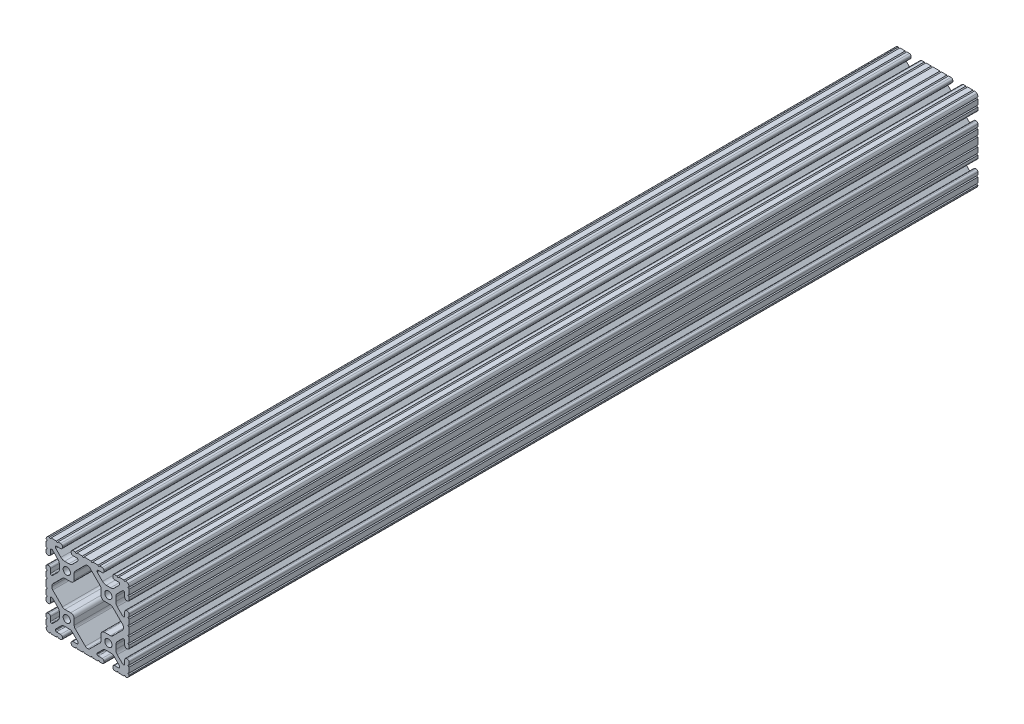
SolidWorks part; units mm, degrees
ref_plane "Front Plane" through (0, 0, 0) normal (0, 0, 1) x (1, 0, 0)
ref_plane "Top Plane" through (0, 0, 0) normal (0, 1, 0) x (1, 0, 0)
ref_plane "Right Plane" through (0, 0, 0) normal (1, 0, 0) x (0, 0, -1)
sketch "Sketch1" plane through (0, 0, 0) normal (0, 0, 1) x (1, 0, 0)
  line L0 (0, 38.1) -> (0, -38.1) construction
  line L1 (-38.1, -38.1) -> (38.1, -38.1) construction
  line L2 (-38.1, -38.1) -> (-38.1, 38.1) construction
  line L3 (-38.1, 38.1) -> (38.1, 38.1) construction
  line L4 (38.1, -38.1) -> (38.1, 38.1) construction
  line L5 (0, 38.1) -> (0, -38.1) construction
  line L6 (-38.1, 0) -> (38.1, 0) construction
  line L7 (-19.05, 19.05) -> (19.05, 19.05) construction
  line L8 (-19.05, 19.05) -> (-19.05, -19.05) construction
  line L9 (-19.05, -19.05) -> (19.05, -19.05) construction
  line L10 (19.05, 19.05) -> (19.05, -19.05) construction
  line L11 (-23.114, 38.1) -> (-23.114, -38.1) construction
  line L12 (-23.114, -38.1) -> (-14.986, 38.1) construction
  line L13 (-14.986, 38.1) -> (-14.986, -38.1) construction
  circle A0 centre (19.05, 19.05) radius 3.3274
  point P0 (0, 0)
  point P9 (0, 0)
  point P12 (-19.05, 0)
  line B0 (-11.3637, -22.8433) -> (-2.0515, -32.1555)
  line B1 (-12.2936, -15.4686) -> (-12.2936, -20.5983)
  line B2 (-20.769, -12.2936) -> (-15.4686, -12.2936)
  line B3 (-31.9021, -2.4756) -> (-23.0141, -11.3637)
  line B4 (-23.0141, 11.3637) -> (-31.9021, 2.4756)
  line B5 (-15.4686, 12.2936) -> (-20.769, 12.2936)
  line B6 (-12.2936, 20.5983) -> (-12.2936, 15.4686)
  line B7 (-2.0515, 32.1555) -> (-11.3637, 22.8433)
  line B8 (11.3637, 22.8433) -> (2.0515, 32.1555)
  line B9 (12.2936, 15.4686) -> (12.2936, 20.5983)
  line B10 (20.769, 12.2936) -> (15.4686, 12.2936)
  line B11 (31.9021, 2.4756) -> (23.0141, 11.3637)
  line B12 (23.0141, -11.3637) -> (31.9021, -2.4756)
  line B13 (15.4686, -12.2936) -> (20.769, -12.2936)
  line B14 (12.2936, -20.5983) -> (12.2936, -15.4686)
  line B15 (2.0515, -32.1555) -> (11.3637, -22.8433)
  line B16 (-4.7773, 38.1) -> (-9.6053, 38.1)
  line B17 (-11.1289, 38.1) -> (-13.4112, 38.1)
  line B18 (-14.986, 36.5252) -> (-14.986, 35.6108)
  line B19 (-13.4112, 34.036) -> (-9.652, 34.036)
  line B20 (-8.763, 33.147) -> (-8.763, 32.4935)
  line B21 (-9.0234, 31.8649) -> (-13.6907, 27.1976)
  line B22 (-17.0493, 25.8064) -> (-21.0507, 25.8064)
  line B23 (-24.4093, 27.1976) -> (-29.1002, 31.8885)
  line B24 (-29.337, 32.7207) -> (-29.337, 33.147)
  line B25 (-28.448, 34.036) -> (-24.6888, 34.036)
  line B26 (-23.114, 35.6108) -> (-23.114, 36.5252)
  line B27 (-24.6888, 38.1) -> (-27.0772, 38.1)
  line B28 (-28.6011, 38.1) -> (-33.4288, 38.1)
  line B29 (-38.1, 33.373) -> (-38.1, 28.5453)
  line B30 (-38.1, 27.0238) -> (-38.1, 24.6302)
  line B31 (-36.5252, 23.0554) -> (-35.6108, 23.0554)
  line B32 (-34.036, 24.6302) -> (-34.036, 28.448)
  line B33 (-33.147, 29.337) -> (-32.6643, 29.337)
  line B34 (-32.0357, 29.0766) -> (-27.1976, 24.2385)
  line B35 (-25.8064, 20.8799) -> (-25.8064, 17.2201)
  line B36 (-27.1976, 13.8615) -> (-31.9489, 9.1101)
  line B37 (-32.7869, 8.763) -> (-33.0603, 8.763)
  line B38 (-34.036, 9.7387) -> (-34.036, 13.4698)
  line B39 (-35.6108, 15.0446) -> (-36.5252, 15.0446)
  line B40 (-38.1, 13.4698) -> (-38.1, 11.075)
  line B41 (-38.1, 9.552) -> (-38.1, 4.7238)
  line B42 (-38.1, 3.2007) -> (-38.1, -3.2007)
  line B43 (-38.1, -4.7238) -> (-38.1, -9.552)
  line B44 (-38.1, -11.075) -> (-38.1, -13.4698)
  line B45 (-36.5252, -15.0446) -> (-35.6108, -15.0446)
  line B46 (-34.036, -13.4698) -> (-34.036, -9.7387)
  line B47 (-33.0603, -8.763) -> (-32.7869, -8.763)
  line B48 (-31.9489, -9.1101) -> (-27.1976, -13.8615)
  line B49 (-25.8064, -17.2201) -> (-25.8064, -20.8799)
  line B50 (-27.1976, -24.2385) -> (-32.0357, -29.0766)
  line B51 (-32.6643, -29.337) -> (-33.147, -29.337)
  line B52 (-34.036, -28.448) -> (-34.036, -24.6302)
  line B53 (-35.6108, -23.0554) -> (-36.5252, -23.0554)
  line B54 (-38.1, -24.6302) -> (-38.1, -27.0238)
  line B55 (-38.1, -28.5453) -> (-38.1, -33.373)
  line B56 (-33.4288, -38.1) -> (-28.6011, -38.1)
  line B57 (-27.0772, -38.1) -> (-24.6888, -38.1)
  line B58 (-23.114, -36.5252) -> (-23.114, -35.6108)
  line B59 (-24.6888, -34.036) -> (-28.448, -34.036)
  line B60 (-29.337, -33.147) -> (-29.337, -32.7207)
  line B61 (-29.1002, -31.8885) -> (-24.4093, -27.1976)
  line B62 (-21.0507, -25.8064) -> (-17.0493, -25.8064)
  line B63 (-13.6907, -27.1976) -> (-9.0234, -31.8649)
  line B64 (-8.763, -32.4935) -> (-8.763, -33.147)
  line B65 (-9.652, -34.036) -> (-13.4112, -34.036)
  line B66 (-14.986, -35.6108) -> (-14.986, -36.5252)
  line B67 (-13.4112, -38.1) -> (-11.1289, -38.1)
  line B68 (-9.6053, -38.1) -> (-4.7773, -38.1)
  line B69 (-3.2537, -38.1) -> (3.2537, -38.1)
  line B70 (4.7773, -38.1) -> (9.6053, -38.1)
  line B71 (11.1289, -38.1) -> (13.4112, -38.1)
  line B72 (14.986, -36.5252) -> (14.986, -35.6108)
  line B73 (13.4112, -34.036) -> (9.652, -34.036)
  line B74 (8.763, -33.147) -> (8.763, -32.4935)
  line B75 (9.0234, -31.8649) -> (13.6907, -27.1976)
  line B76 (17.0493, -25.8064) -> (21.0507, -25.8064)
  line B77 (24.4093, -27.1976) -> (29.1002, -31.8885)
  line B78 (29.337, -32.7207) -> (29.337, -33.147)
  line B79 (28.448, -34.036) -> (24.6888, -34.036)
  line B80 (23.114, -35.6108) -> (23.114, -36.5252)
  line B81 (24.6888, -38.1) -> (27.0772, -38.1)
  line B82 (28.6011, -38.1) -> (33.4288, -38.1)
  line B83 (38.1, -33.373) -> (38.1, -28.5453)
  line B84 (38.1, -27.0238) -> (38.1, -24.6302)
  line B85 (36.5252, -23.0554) -> (35.6108, -23.0554)
  line B86 (34.036, -24.6302) -> (34.036, -28.448)
  line B87 (33.147, -29.337) -> (32.6643, -29.337)
  line B88 (32.0357, -29.0766) -> (27.1976, -24.2385)
  line B89 (25.8064, -20.8799) -> (25.8064, -17.2201)
  line B90 (27.1976, -13.8615) -> (31.9489, -9.1101)
  line B91 (32.7869, -8.763) -> (33.0603, -8.763)
  line B92 (34.036, -9.7387) -> (34.036, -13.4698)
  line B93 (35.6108, -15.0446) -> (36.5252, -15.0446)
  line B94 (38.1, -13.4698) -> (38.1, -11.075)
  line B95 (38.1, -9.552) -> (38.1, -4.7238)
  line B96 (38.1, -3.2007) -> (38.1, 3.2007)
  line B97 (38.1, 4.7238) -> (38.1, 9.552)
  line B98 (38.1, 11.075) -> (38.1, 13.4698)
  line B99 (36.5252, 15.0446) -> (35.6108, 15.0446)
  line B100 (34.036, 13.4698) -> (34.036, 9.7387)
  line B101 (33.0603, 8.763) -> (32.7869, 8.763)
  line B102 (31.9489, 9.1101) -> (27.1976, 13.8615)
  line B103 (25.8064, 17.2201) -> (25.8064, 20.8799)
  line B104 (27.1976, 24.2385) -> (32.0357, 29.0766)
  line B105 (32.6643, 29.337) -> (33.147, 29.337)
  line B106 (34.036, 28.448) -> (34.036, 24.6302)
  line B107 (35.6108, 23.0554) -> (36.5252, 23.0554)
  line B108 (38.1, 24.6302) -> (38.1, 27.0238)
  line B109 (38.1, 28.5453) -> (38.1, 33.373)
  line B110 (33.4288, 38.1) -> (28.6011, 38.1)
  line B111 (27.0772, 38.1) -> (24.6888, 38.1)
  line B112 (23.114, 36.5252) -> (23.114, 35.6108)
  line B113 (24.6888, 34.036) -> (28.448, 34.036)
  line B114 (29.337, 33.147) -> (29.337, 32.7207)
  line B115 (29.1002, 31.8885) -> (24.4093, 27.1976)
  line B116 (21.0507, 25.8064) -> (17.0493, 25.8064)
  line B117 (13.6907, 27.1976) -> (9.0234, 31.8649)
  line B118 (8.763, 32.4935) -> (8.763, 33.147)
  line B119 (9.652, 34.036) -> (13.4112, 34.036)
  line B120 (14.986, 35.6108) -> (14.986, 36.5252)
  line B121 (13.4112, 38.1) -> (11.1289, 38.1)
  line B122 (9.6053, 38.1) -> (4.7773, 38.1)
  line B123 (3.2537, 38.1) -> (-3.2537, 38.1)
  circle B124 centre (-19.05, 19.05) radius 3.3274
  circle B125 centre (-19.05, -19.05) radius 3.3274
  circle B126 centre (19.05, -19.05) radius 3.3274
  circle B127 centre (19.05, 19.05) radius 3.3274
  arc B128 (0, -33.011) -> (2.0515, -32.1555) centre (-0.0139, -30.09) ccw
  arc B129 (-2.0515, -32.1555) -> (0, -33.011) centre (0.0139, -30.09) ccw
  arc B130 (-12.2936, -20.5983) -> (-11.3637, -22.8433) centre (-9.1186, -20.5983) ccw
  arc B131 (-12.2936, -15.4686) -> (-15.4686, -12.2936) centre (-15.4686, -15.4686) ccw
  arc B132 (-23.0141, -11.3637) -> (-20.769, -12.2936) centre (-20.769, -9.1186) ccw
  arc B133 (-32.7287, 0) -> (-31.9021, -2.4756) centre (-29.8367, -0.4102) ccw
  arc B134 (-31.9021, 2.4756) -> (-32.7287, 0) centre (-29.8367, 0.4102) ccw
  arc B135 (-20.769, 12.2936) -> (-23.0141, 11.3637) centre (-20.769, 9.1186) ccw
  arc B136 (-15.4686, 12.2936) -> (-12.2936, 15.4686) centre (-15.4686, 15.4686) ccw
  arc B137 (-11.3637, 22.8433) -> (-12.2936, 20.5983) centre (-9.1186, 20.5983) ccw
  arc B138 (0, 33.011) -> (-2.0515, 32.1555) centre (0.0139, 30.09) ccw
  arc B139 (2.0515, 32.1555) -> (0, 33.011) centre (-0.0139, 30.09) ccw
  arc B140 (12.2936, 20.5983) -> (11.3637, 22.8433) centre (9.1186, 20.5983) ccw
  arc B141 (12.2936, 15.4686) -> (15.4686, 12.2936) centre (15.4686, 15.4686) ccw
  arc B142 (23.0141, 11.3637) -> (20.769, 12.2936) centre (20.769, 9.1186) ccw
  arc B143 (32.7287, 0) -> (31.9021, 2.4756) centre (29.8367, 0.4102) ccw
  arc B144 (31.9021, -2.4756) -> (32.7287, 0) centre (29.8367, -0.4102) ccw
  arc B145 (20.769, -12.2936) -> (23.0141, -11.3637) centre (20.769, -9.1186) ccw
  arc B146 (15.4686, -12.2936) -> (12.2936, -15.4686) centre (15.4686, -15.4686) ccw
  arc B147 (11.3637, -22.8433) -> (12.2936, -20.5983) centre (9.1186, -20.5983) ccw
  arc B148 (-4.7773, 38.1) -> (-3.2537, 38.1) centre (-4.0155, 38.0824) ccw
  arc B149 (-11.1289, 38.1) -> (-9.6053, 38.1) centre (-10.3671, 38.0824) ccw
  arc B150 (-13.4112, 38.1) -> (-14.986, 36.5252) centre (-13.4112, 36.5252) ccw
  arc B151 (-14.986, 35.6108) -> (-13.4112, 34.036) centre (-13.4112, 35.6108) ccw
  arc B152 (-8.763, 33.147) -> (-9.652, 34.036) centre (-9.652, 33.147) ccw
  arc B153 (-9.0234, 31.8649) -> (-8.763, 32.4935) centre (-9.652, 32.4935) ccw
  arc B154 (-17.0493, 25.8064) -> (-13.6907, 27.1976) centre (-17.0493, 30.5562) ccw
  arc B155 (-24.4093, 27.1976) -> (-21.0507, 25.8064) centre (-21.0507, 30.5562) ccw
  arc B156 (-29.337, 32.7207) -> (-29.1002, 31.8885) centre (-28.4716, 32.5172) ccw
  arc B157 (-28.448, 34.036) -> (-29.337, 33.147) centre (-28.448, 33.147) ccw
  arc B158 (-24.6888, 34.036) -> (-23.114, 35.6108) centre (-24.6888, 35.6108) ccw
  arc B159 (-23.114, 36.5252) -> (-24.6888, 38.1) centre (-24.6888, 36.5252) ccw
  arc B160 (-28.6011, 38.1) -> (-27.0772, 38.1) centre (-27.8392, 38.0824) ccw
  arc B161 (-34.9527, 38.1) -> (-33.4288, 38.1) centre (-34.1907, 38.0824) ccw
  arc B162 (-34.9527, 38.1) -> (-37.0861, 37.1826) centre (-34.8521, 34.9266) ccw
  arc B163 (-37.0861, 37.1826) -> (-38.1, 34.8455) centre (-34.925, 34.8566) ccw
  arc B164 (-38.1, 33.373) -> (-38.1, 34.8455) centre (-37.9035, 34.1092) ccw
  arc B165 (-38.1, 27.0238) -> (-38.1, 28.5453) centre (-37.9035, 27.7845) ccw
  arc B166 (-38.1, 24.6302) -> (-36.5252, 23.0554) centre (-36.5252, 24.6302) ccw
  arc B167 (-35.6108, 23.0554) -> (-34.036, 24.6302) centre (-35.6108, 24.6302) ccw
  arc B168 (-33.147, 29.337) -> (-34.036, 28.448) centre (-33.147, 28.448) ccw
  arc B169 (-32.0357, 29.0766) -> (-32.6643, 29.337) centre (-32.6643, 28.448) ccw
  arc B170 (-25.8064, 20.8799) -> (-27.1976, 24.2385) centre (-30.5562, 20.8799) ccw
  arc B171 (-27.1976, 13.8615) -> (-25.8064, 17.2201) centre (-30.5562, 17.2201) ccw
  arc B172 (-32.7869, 8.763) -> (-31.9489, 9.1101) centre (-32.7869, 9.9481) ccw
  arc B173 (-34.036, 9.7387) -> (-33.0603, 8.763) centre (-33.0603, 9.7387) ccw
  arc B174 (-34.036, 13.4698) -> (-35.6108, 15.0446) centre (-35.6108, 13.4698) ccw
  arc B175 (-36.5252, 15.0446) -> (-38.1, 13.4698) centre (-36.5252, 13.4698) ccw
  arc B176 (-38.1, 9.552) -> (-38.1, 11.075) centre (-37.9035, 10.3135) ccw
  arc B177 (-38.1, 3.2007) -> (-38.1, 4.7238) centre (-37.9035, 3.9622) ccw
  arc B178 (-38.1, -4.7238) -> (-38.1, -3.2007) centre (-37.9035, -3.9622) ccw
  arc B179 (-38.1, -11.075) -> (-38.1, -9.552) centre (-37.9035, -10.3135) ccw
  arc B180 (-38.1, -13.4698) -> (-36.5252, -15.0446) centre (-36.5252, -13.4698) ccw
  arc B181 (-35.6108, -15.0446) -> (-34.036, -13.4698) centre (-35.6108, -13.4698) ccw
  arc B182 (-33.0603, -8.763) -> (-34.036, -9.7387) centre (-33.0603, -9.7387) ccw
  arc B183 (-31.9489, -9.1101) -> (-32.7869, -8.763) centre (-32.7869, -9.9481) ccw
  arc B184 (-25.8064, -17.2201) -> (-27.1976, -13.8615) centre (-30.5562, -17.2201) ccw
  arc B185 (-27.1976, -24.2385) -> (-25.8064, -20.8799) centre (-30.5562, -20.8799) ccw
  arc B186 (-32.6643, -29.337) -> (-32.0357, -29.0766) centre (-32.6643, -28.448) ccw
  arc B187 (-34.036, -28.448) -> (-33.147, -29.337) centre (-33.147, -28.448) ccw
  arc B188 (-34.036, -24.6302) -> (-35.6108, -23.0554) centre (-35.6108, -24.6302) ccw
  arc B189 (-36.5252, -23.0554) -> (-38.1, -24.6302) centre (-36.5252, -24.6302) ccw
  arc B190 (-38.1, -28.5453) -> (-38.1, -27.0238) centre (-37.9035, -27.7845) ccw
  arc B191 (-38.1, -34.8455) -> (-38.1, -33.373) centre (-37.9035, -34.1092) ccw
  arc B192 (-38.1, -34.8455) -> (-37.0861, -37.1826) centre (-34.925, -34.8566) ccw
  arc B193 (-37.0861, -37.1826) -> (-34.9527, -38.1) centre (-34.8521, -34.9266) ccw
  arc B194 (-33.4288, -38.1) -> (-34.9527, -38.1) centre (-34.1907, -38.0824) ccw
  arc B195 (-27.0772, -38.1) -> (-28.6011, -38.1) centre (-27.8392, -38.0824) ccw
  arc B196 (-24.6888, -38.1) -> (-23.114, -36.5252) centre (-24.6888, -36.5252) ccw
  arc B197 (-23.114, -35.6108) -> (-24.6888, -34.036) centre (-24.6888, -35.6108) ccw
  arc B198 (-29.337, -33.147) -> (-28.448, -34.036) centre (-28.448, -33.147) ccw
  arc B199 (-29.1002, -31.8885) -> (-29.337, -32.7207) centre (-28.4716, -32.5172) ccw
  arc B200 (-21.0507, -25.8064) -> (-24.4093, -27.1976) centre (-21.0507, -30.5562) ccw
  arc B201 (-13.6907, -27.1976) -> (-17.0493, -25.8064) centre (-17.0493, -30.5562) ccw
  arc B202 (-8.763, -32.4935) -> (-9.0234, -31.8649) centre (-9.652, -32.4935) ccw
  arc B203 (-9.652, -34.036) -> (-8.763, -33.147) centre (-9.652, -33.147) ccw
  arc B204 (-13.4112, -34.036) -> (-14.986, -35.6108) centre (-13.4112, -35.6108) ccw
  arc B205 (-14.986, -36.5252) -> (-13.4112, -38.1) centre (-13.4112, -36.5252) ccw
  arc B206 (-9.6053, -38.1) -> (-11.1289, -38.1) centre (-10.3671, -38.0824) ccw
  arc B207 (-3.2537, -38.1) -> (-4.7773, -38.1) centre (-4.0155, -38.0824) ccw
  arc B208 (4.7773, -38.1) -> (3.2537, -38.1) centre (4.0155, -38.0824) ccw
  arc B209 (11.1289, -38.1) -> (9.6053, -38.1) centre (10.3671, -38.0824) ccw
  arc B210 (13.4112, -38.1) -> (14.986, -36.5252) centre (13.4112, -36.5252) ccw
  arc B211 (14.986, -35.6108) -> (13.4112, -34.036) centre (13.4112, -35.6108) ccw
  arc B212 (8.763, -33.147) -> (9.652, -34.036) centre (9.652, -33.147) ccw
  arc B213 (9.0234, -31.8649) -> (8.763, -32.4935) centre (9.652, -32.4935) ccw
  arc B214 (17.0493, -25.8064) -> (13.6907, -27.1976) centre (17.0493, -30.5562) ccw
  arc B215 (24.4093, -27.1976) -> (21.0507, -25.8064) centre (21.0507, -30.5562) ccw
  arc B216 (29.337, -32.7207) -> (29.1002, -31.8885) centre (28.4716, -32.5172) ccw
  arc B217 (28.448, -34.036) -> (29.337, -33.147) centre (28.448, -33.147) ccw
  arc B218 (24.6888, -34.036) -> (23.114, -35.6108) centre (24.6888, -35.6108) ccw
  arc B219 (23.114, -36.5252) -> (24.6888, -38.1) centre (24.6888, -36.5252) ccw
  arc B220 (28.6011, -38.1) -> (27.0772, -38.1) centre (27.8392, -38.0824) ccw
  arc B221 (34.9527, -38.1) -> (33.4288, -38.1) centre (34.1907, -38.0824) ccw
  arc B222 (34.9527, -38.1) -> (37.0861, -37.1826) centre (34.8521, -34.9266) ccw
  arc B223 (37.0861, -37.1826) -> (38.1, -34.8455) centre (34.925, -34.8566) ccw
  arc B224 (38.1, -33.373) -> (38.1, -34.8455) centre (37.9035, -34.1092) ccw
  arc B225 (38.1, -27.0238) -> (38.1, -28.5453) centre (37.9035, -27.7845) ccw
  arc B226 (38.1, -24.6302) -> (36.5252, -23.0554) centre (36.5252, -24.6302) ccw
  arc B227 (35.6108, -23.0554) -> (34.036, -24.6302) centre (35.6108, -24.6302) ccw
  arc B228 (33.147, -29.337) -> (34.036, -28.448) centre (33.147, -28.448) ccw
  arc B229 (32.0357, -29.0766) -> (32.6643, -29.337) centre (32.6643, -28.448) ccw
  arc B230 (25.8064, -20.8799) -> (27.1976, -24.2385) centre (30.5562, -20.8799) ccw
  arc B231 (27.1976, -13.8615) -> (25.8064, -17.2201) centre (30.5562, -17.2201) ccw
  arc B232 (32.7869, -8.763) -> (31.9489, -9.1101) centre (32.7869, -9.9481) ccw
  arc B233 (34.036, -9.7387) -> (33.0603, -8.763) centre (33.0603, -9.7387) ccw
  arc B234 (34.036, -13.4698) -> (35.6108, -15.0446) centre (35.6108, -13.4698) ccw
  arc B235 (36.5252, -15.0446) -> (38.1, -13.4698) centre (36.5252, -13.4698) ccw
  arc B236 (38.1, -9.552) -> (38.1, -11.075) centre (37.9035, -10.3135) ccw
  arc B237 (38.1, -3.2007) -> (38.1, -4.7238) centre (37.9035, -3.9622) ccw
  arc B238 (38.1, 4.7238) -> (38.1, 3.2007) centre (37.9035, 3.9622) ccw
  arc B239 (38.1, 11.075) -> (38.1, 9.552) centre (37.9035, 10.3135) ccw
  arc B240 (38.1, 13.4698) -> (36.5252, 15.0446) centre (36.5252, 13.4698) ccw
  arc B241 (35.6108, 15.0446) -> (34.036, 13.4698) centre (35.6108, 13.4698) ccw
  arc B242 (33.0603, 8.763) -> (34.036, 9.7387) centre (33.0603, 9.7387) ccw
  arc B243 (31.9489, 9.1101) -> (32.7869, 8.763) centre (32.7869, 9.9481) ccw
  arc B244 (25.8064, 17.2201) -> (27.1976, 13.8615) centre (30.5562, 17.2201) ccw
  arc B245 (27.1976, 24.2385) -> (25.8064, 20.8799) centre (30.5562, 20.8799) ccw
  arc B246 (32.6643, 29.337) -> (32.0357, 29.0766) centre (32.6643, 28.448) ccw
  arc B247 (34.036, 28.448) -> (33.147, 29.337) centre (33.147, 28.448) ccw
  arc B248 (34.036, 24.6302) -> (35.6108, 23.0554) centre (35.6108, 24.6302) ccw
  arc B249 (36.5252, 23.0554) -> (38.1, 24.6302) centre (36.5252, 24.6302) ccw
  arc B250 (38.1, 28.5453) -> (38.1, 27.0238) centre (37.9035, 27.7845) ccw
  arc B251 (38.1, 34.8455) -> (38.1, 33.373) centre (37.9035, 34.1092) ccw
  arc B252 (38.1, 34.8455) -> (37.0861, 37.1826) centre (34.925, 34.8566) ccw
  arc B253 (37.0861, 37.1826) -> (34.9527, 38.1) centre (34.8521, 34.9266) ccw
  arc B254 (33.4288, 38.1) -> (34.9527, 38.1) centre (34.1907, 38.0824) ccw
  arc B255 (27.0772, 38.1) -> (28.6011, 38.1) centre (27.8392, 38.0824) ccw
  arc B256 (24.6888, 38.1) -> (23.114, 36.5252) centre (24.6888, 36.5252) ccw
  arc B257 (23.114, 35.6108) -> (24.6888, 34.036) centre (24.6888, 35.6108) ccw
  arc B258 (29.337, 33.147) -> (28.448, 34.036) centre (28.448, 33.147) ccw
  arc B259 (29.1002, 31.8885) -> (29.337, 32.7207) centre (28.4716, 32.5172) ccw
  arc B260 (21.0507, 25.8064) -> (24.4093, 27.1976) centre (21.0507, 30.5562) ccw
  arc B261 (13.6907, 27.1976) -> (17.0493, 25.8064) centre (17.0493, 30.5562) ccw
  arc B262 (8.763, 32.4935) -> (9.0234, 31.8649) centre (9.652, 32.4935) ccw
  arc B263 (9.652, 34.036) -> (8.763, 33.147) centre (9.652, 33.147) ccw
  arc B264 (13.4112, 34.036) -> (14.986, 35.6108) centre (13.4112, 35.6108) ccw
  arc B265 (14.986, 36.5252) -> (13.4112, 38.1) centre (13.4112, 36.5252) ccw
  arc B266 (9.6053, 38.1) -> (11.1289, 38.1) centre (10.3671, 38.0824) ccw
  arc B267 (3.2537, 38.1) -> (4.7773, 38.1) centre (4.0155, 38.0824) ccw
  dimension "Center Hole Diameter" = 6.6548
  dimension "Rail Width" = 76.2
  dimension "Rail Height" = 76.2
  dimension "T-Slot Width" = 8.128
sketch_block_instance "Block1-1"
sketch_block "Block1"
sketch "Sketch2" plane through (0, 0, 0) normal (1, 0, 0) x (0, 0, -1)
  line L0 (-388.8, 0) -> (388.8, 0) construction
  line L1 (-388.8, 38.1) -> (-388.8, -38.1) construction
  line L2 (-388.8, -38.1) -> (388.8, -38.1) construction
  line L3 (388.8, -38.1) -> (388.8, 38.1) construction
  line L4 (-287.2, 0) -> (-287.2, 38.1) construction
  line L5 (-287.2, 38.1) -> (287.2, 38.1) construction
  line L6 (287.2, 38.1) -> (287.2, 0) construction
  point P5 (287.2, 0)
  point P10 (-287.2, 0)
  dimension "D1" = 101.6
  dimension "Length" = 777.6
  dimension "D2" = 101.6
sketch "Sketch3" plane through (0, 0, 0) normal (0, 0, 1) x (1, 0, 0)
  line L0 (-11.3637, -22.8433) -> (-2.0515, -32.1555) construction
  line L1 (-12.2936, -15.4686) -> (-12.2936, -20.5983) construction
  line L2 (-20.769, -12.2936) -> (-15.4686, -12.2936) construction
  line L3 (-31.9021, -2.4756) -> (-23.0141, -11.3637) construction
  line L4 (-23.0141, 11.3637) -> (-31.9021, 2.4756) construction
  line L5 (-15.4686, 12.2936) -> (-20.769, 12.2936) construction
  line L6 (-12.2936, 20.5983) -> (-12.2936, 15.4686) construction
  line L7 (-2.0515, 32.1555) -> (-11.3637, 22.8433) construction
  line L8 (11.3637, 22.8433) -> (2.0515, 32.1555) construction
  line L9 (12.2936, 15.4686) -> (12.2936, 20.5983) construction
  line L10 (20.769, 12.2936) -> (15.4686, 12.2936) construction
  line L11 (31.9021, 2.4756) -> (23.0141, 11.3637) construction
  line L12 (23.0141, -11.3637) -> (31.9021, -2.4756) construction
  line L13 (15.4686, -12.2936) -> (20.769, -12.2936) construction
  line L14 (12.2936, -20.5983) -> (12.2936, -15.4686) construction
  line L15 (2.0515, -32.1555) -> (11.3637, -22.8433) construction
  line L16 (34.036, 28.448) -> (34.036, 24.6302) construction
  line L17 (35.6108, 23.0554) -> (36.5252, 23.0554) construction
  line L18 (38.1, 24.6302) -> (38.1, 27.0238) construction
  line L19 (38.1, 28.5453) -> (38.1, 33.373) construction
  line L20 (33.4288, 38.1) -> (28.6011, 38.1) construction
  line L21 (27.0772, 38.1) -> (24.6888, 38.1) construction
  line L22 (23.114, 36.5252) -> (23.114, 35.6108) construction
  line L23 (24.6888, 34.036) -> (28.448, 34.036) construction
  line L24 (29.337, 33.147) -> (29.337, 32.7207) construction
  line L25 (29.1002, 31.8885) -> (24.4093, 27.1976) construction
  line L26 (21.0507, 25.8064) -> (17.0493, 25.8064) construction
  line L27 (13.6907, 27.1976) -> (9.0234, 31.8649) construction
  line L28 (8.763, 32.4935) -> (8.763, 33.147) construction
  line L29 (9.652, 34.036) -> (13.4112, 34.036) construction
  line L30 (14.986, 35.6108) -> (14.986, 36.5252) construction
  line L31 (13.4112, 38.1) -> (11.1289, 38.1) construction
  line L32 (9.6053, 38.1) -> (4.7773, 38.1) construction
  line L33 (3.2537, 38.1) -> (-3.2537, 38.1) construction
  line L34 (-4.7773, 38.1) -> (-9.6053, 38.1) construction
  line L35 (-11.1289, 38.1) -> (-13.4112, 38.1) construction
  line L36 (-14.986, 36.5252) -> (-14.986, 35.6108) construction
  line L37 (-13.4112, 34.036) -> (-9.652, 34.036) construction
  line L38 (-8.763, 33.147) -> (-8.763, 32.4935) construction
  line L39 (-9.0234, 31.8649) -> (-13.6907, 27.1976) construction
  line L40 (-17.0493, 25.8064) -> (-21.0507, 25.8064) construction
  line L41 (-24.4093, 27.1976) -> (-29.1002, 31.8885) construction
  line L42 (-29.337, 32.7207) -> (-29.337, 33.147) construction
  line L43 (-28.448, 34.036) -> (-24.6888, 34.036) construction
  line L44 (-23.114, 35.6108) -> (-23.114, 36.5252) construction
  line L45 (-24.6888, 38.1) -> (-27.0772, 38.1) construction
  line L46 (-28.6011, 38.1) -> (-33.4288, 38.1) construction
  line L47 (-38.1, 33.373) -> (-38.1, 28.5453) construction
  line L48 (-38.1, 27.0238) -> (-38.1, 24.6302) construction
  line L49 (-36.5252, 23.0554) -> (-35.6108, 23.0554) construction
  line L50 (-34.036, 24.6302) -> (-34.036, 28.448) construction
  line L51 (-33.147, 29.337) -> (-32.6643, 29.337) construction
  line L52 (-32.0357, 29.0766) -> (-27.1976, 24.2385) construction
  line L53 (-25.8064, 20.8799) -> (-25.8064, 17.2201) construction
  line L54 (-27.1976, 13.8615) -> (-31.9489, 9.1101) construction
  line L55 (-32.7869, 8.763) -> (-33.0603, 8.763) construction
  line L56 (-34.036, 9.7387) -> (-34.036, 13.4698) construction
  line L57 (-35.6108, 15.0446) -> (-36.5252, 15.0446) construction
  line L58 (-38.1, 13.4698) -> (-38.1, 11.075) construction
  line L59 (-38.1, 9.552) -> (-38.1, 4.7238) construction
  line L60 (-38.1, 3.2007) -> (-38.1, -3.2007) construction
  line L61 (-38.1, -4.7238) -> (-38.1, -9.552) construction
  line L62 (-38.1, -11.075) -> (-38.1, -13.4698) construction
  line L63 (-36.5252, -15.0446) -> (-35.6108, -15.0446) construction
  line L64 (-34.036, -13.4698) -> (-34.036, -9.7387) construction
  line L65 (-33.0603, -8.763) -> (-32.7869, -8.763) construction
  line L66 (-31.9489, -9.1101) -> (-27.1976, -13.8615) construction
  line L67 (-25.8064, -17.2201) -> (-25.8064, -20.8799) construction
  line L68 (-27.1976, -24.2385) -> (-32.0357, -29.0766) construction
  line L69 (-32.6643, -29.337) -> (-33.147, -29.337) construction
  line L70 (-34.036, -28.448) -> (-34.036, -24.6302) construction
  line L71 (-35.6108, -23.0554) -> (-36.5252, -23.0554) construction
  line L72 (-38.1, -24.6302) -> (-38.1, -27.0238) construction
  line L73 (-38.1, -28.5453) -> (-38.1, -33.373) construction
  line L74 (-33.4288, -38.1) -> (-28.6011, -38.1) construction
  line L75 (-27.0772, -38.1) -> (-24.6888, -38.1) construction
  line L76 (-23.114, -36.5252) -> (-23.114, -35.6108) construction
  line L77 (-24.6888, -34.036) -> (-28.448, -34.036) construction
  line L78 (-29.337, -33.147) -> (-29.337, -32.7207) construction
  line L79 (-29.1002, -31.8885) -> (-24.4093, -27.1976) construction
  line L80 (-21.0507, -25.8064) -> (-17.0493, -25.8064) construction
  line L81 (-13.6907, -27.1976) -> (-9.0234, -31.8649) construction
  line L82 (-8.763, -32.4935) -> (-8.763, -33.147) construction
  line L83 (-9.652, -34.036) -> (-13.4112, -34.036) construction
  line L84 (-14.986, -35.6108) -> (-14.986, -36.5252) construction
  line L85 (-13.4112, -38.1) -> (-11.1289, -38.1) construction
  line L86 (-9.6053, -38.1) -> (-4.7773, -38.1) construction
  line L87 (-3.2537, -38.1) -> (3.2537, -38.1) construction
  line L88 (4.7773, -38.1) -> (9.6053, -38.1) construction
  line L89 (11.1289, -38.1) -> (13.4112, -38.1) construction
  line L90 (14.986, -36.5252) -> (14.986, -35.6108) construction
  line L91 (13.4112, -34.036) -> (9.652, -34.036) construction
  line L92 (8.763, -33.147) -> (8.763, -32.4935) construction
  line L93 (9.0234, -31.8649) -> (13.6907, -27.1976) construction
  line L94 (17.0493, -25.8064) -> (21.0507, -25.8064) construction
  line L95 (24.4093, -27.1976) -> (29.1002, -31.8885) construction
  line L96 (29.337, -32.7207) -> (29.337, -33.147) construction
  line L97 (28.448, -34.036) -> (24.6888, -34.036) construction
  line L98 (23.114, -35.6108) -> (23.114, -36.5252) construction
  line L99 (24.6888, -38.1) -> (27.0772, -38.1) construction
  line L100 (28.6011, -38.1) -> (33.4288, -38.1) construction
  line L101 (38.1, -33.373) -> (38.1, -28.5453) construction
  line L102 (38.1, -27.0238) -> (38.1, -24.6302) construction
  line L103 (36.5252, -23.0554) -> (35.6108, -23.0554) construction
  line L104 (34.036, -24.6302) -> (34.036, -28.448) construction
  line L105 (33.147, -29.337) -> (32.6643, -29.337) construction
  line L106 (32.0357, -29.0766) -> (27.1976, -24.2385) construction
  line L107 (25.8064, -20.8799) -> (25.8064, -17.2201) construction
  line L108 (27.1976, -13.8615) -> (31.9489, -9.1101) construction
  line L109 (32.7869, -8.763) -> (33.0603, -8.763) construction
  line L110 (34.036, -9.7387) -> (34.036, -13.4698) construction
  line L111 (35.6108, -15.0446) -> (36.5252, -15.0446) construction
  line L112 (38.1, -13.4698) -> (38.1, -11.075) construction
  line L113 (38.1, -9.552) -> (38.1, -4.7238) construction
  line L114 (38.1, -3.2007) -> (38.1, 3.2007) construction
  line L115 (38.1, 4.7238) -> (38.1, 9.552) construction
  line L116 (38.1, 11.075) -> (38.1, 13.4698) construction
  line L117 (36.5252, 15.0446) -> (35.6108, 15.0446) construction
  line L118 (34.036, 13.4698) -> (34.036, 9.7387) construction
  line L119 (33.0603, 8.763) -> (32.7869, 8.763) construction
  line L120 (31.9489, 9.1101) -> (27.1976, 13.8615) construction
  line L121 (25.8064, 17.2201) -> (25.8064, 20.8799) construction
  line L122 (27.1976, 24.2385) -> (32.0357, 29.0766) construction
  line L123 (32.6643, 29.337) -> (33.147, 29.337) construction
  line L124 (-11.3637, -22.8433) -> (-2.0515, -32.1555)
  line L125 (-12.2936, -15.4686) -> (-12.2936, -20.5983)
  line L126 (-20.769, -12.2936) -> (-15.4686, -12.2936)
  line L127 (-31.9021, -2.4756) -> (-23.0141, -11.3637)
  line L128 (-23.0141, 11.3637) -> (-31.9021, 2.4756)
  line L129 (-15.4686, 12.2936) -> (-20.769, 12.2936)
  line L130 (-12.2936, 20.5983) -> (-12.2936, 15.4686)
  line L131 (-2.0515, 32.1555) -> (-11.3637, 22.8433)
  line L132 (11.3637, 22.8433) -> (2.0515, 32.1555)
  line L133 (12.2936, 15.4686) -> (12.2936, 20.5983)
  line L134 (20.769, 12.2936) -> (15.4686, 12.2936)
  line L135 (31.9021, 2.4756) -> (23.0141, 11.3637)
  line L136 (23.0141, -11.3637) -> (31.9021, -2.4756)
  line L137 (15.4686, -12.2936) -> (20.769, -12.2936)
  line L138 (12.2936, -20.5983) -> (12.2936, -15.4686)
  line L139 (2.0515, -32.1555) -> (11.3637, -22.8433)
  line L140 (34.036, 28.448) -> (34.036, 24.6302)
  line L141 (35.6108, 23.0554) -> (36.5252, 23.0554)
  line L142 (38.1, 24.6302) -> (38.1, 27.0238)
  line L143 (38.1, 28.5453) -> (38.1, 33.373)
  line L144 (33.4288, 38.1) -> (28.6011, 38.1)
  line L145 (27.0772, 38.1) -> (24.6888, 38.1)
  line L146 (23.114, 36.5252) -> (23.114, 35.6108)
  line L147 (24.6888, 34.036) -> (28.448, 34.036)
  line L148 (29.337, 33.147) -> (29.337, 32.7207)
  line L149 (29.1002, 31.8885) -> (24.4093, 27.1976)
  line L150 (21.0507, 25.8064) -> (17.0493, 25.8064)
  line L151 (13.6907, 27.1976) -> (9.0234, 31.8649)
  line L152 (8.763, 32.4935) -> (8.763, 33.147)
  line L153 (9.652, 34.036) -> (13.4112, 34.036)
  line L154 (14.986, 35.6108) -> (14.986, 36.5252)
  line L155 (13.4112, 38.1) -> (11.1289, 38.1)
  line L156 (9.6053, 38.1) -> (4.7773, 38.1)
  line L157 (3.2537, 38.1) -> (-3.2537, 38.1)
  line L158 (-4.7773, 38.1) -> (-9.6053, 38.1)
  line L159 (-11.1289, 38.1) -> (-13.4112, 38.1)
  line L160 (-14.986, 36.5252) -> (-14.986, 35.6108)
  line L161 (-13.4112, 34.036) -> (-9.652, 34.036)
  line L162 (-8.763, 33.147) -> (-8.763, 32.4935)
  line L163 (-9.0234, 31.8649) -> (-13.6907, 27.1976)
  line L164 (-17.0493, 25.8064) -> (-21.0507, 25.8064)
  line L165 (-24.4093, 27.1976) -> (-29.1002, 31.8885)
  line L166 (-29.337, 32.7207) -> (-29.337, 33.147)
  line L167 (-28.448, 34.036) -> (-24.6888, 34.036)
  line L168 (-23.114, 35.6108) -> (-23.114, 36.5252)
  line L169 (-24.6888, 38.1) -> (-27.0772, 38.1)
  line L170 (-28.6011, 38.1) -> (-33.4288, 38.1)
  line L171 (-38.1, 33.373) -> (-38.1, 28.5453)
  line L172 (-38.1, 27.0238) -> (-38.1, 24.6302)
  line L173 (-36.5252, 23.0554) -> (-35.6108, 23.0554)
  line L174 (-34.036, 24.6302) -> (-34.036, 28.448)
  line L175 (-33.147, 29.337) -> (-32.6643, 29.337)
  line L176 (-32.0357, 29.0766) -> (-27.1976, 24.2385)
  line L177 (-25.8064, 20.8799) -> (-25.8064, 17.2201)
  line L178 (-27.1976, 13.8615) -> (-31.9489, 9.1101)
  line L179 (-32.7869, 8.763) -> (-33.0603, 8.763)
  line L180 (-34.036, 9.7387) -> (-34.036, 13.4698)
  line L181 (-35.6108, 15.0446) -> (-36.5252, 15.0446)
  line L182 (-38.1, 13.4698) -> (-38.1, 11.075)
  line L183 (-38.1, 9.552) -> (-38.1, 4.7238)
  line L184 (-38.1, 3.2007) -> (-38.1, -3.2007)
  line L185 (-38.1, -4.7238) -> (-38.1, -9.552)
  line L186 (-38.1, -11.075) -> (-38.1, -13.4698)
  line L187 (-36.5252, -15.0446) -> (-35.6108, -15.0446)
  line L188 (-34.036, -13.4698) -> (-34.036, -9.7387)
  line L189 (-33.0603, -8.763) -> (-32.7869, -8.763)
  line L190 (-31.9489, -9.1101) -> (-27.1976, -13.8615)
  line L191 (-25.8064, -17.2201) -> (-25.8064, -20.8799)
  line L192 (-27.1976, -24.2385) -> (-32.0357, -29.0766)
  line L193 (-32.6643, -29.337) -> (-33.147, -29.337)
  line L194 (-34.036, -28.448) -> (-34.036, -24.6302)
  line L195 (-35.6108, -23.0554) -> (-36.5252, -23.0554)
  line L196 (-38.1, -24.6302) -> (-38.1, -27.0238)
  line L197 (-38.1, -28.5453) -> (-38.1, -33.373)
  line L198 (-33.4288, -38.1) -> (-28.6011, -38.1)
  line L199 (-27.0772, -38.1) -> (-24.6888, -38.1)
  line L200 (-23.114, -36.5252) -> (-23.114, -35.6108)
  line L201 (-24.6888, -34.036) -> (-28.448, -34.036)
  line L202 (-29.337, -33.147) -> (-29.337, -32.7207)
  line L203 (-29.1002, -31.8885) -> (-24.4093, -27.1976)
  line L204 (-21.0507, -25.8064) -> (-17.0493, -25.8064)
  line L205 (-13.6907, -27.1976) -> (-9.0234, -31.8649)
  line L206 (-8.763, -32.4935) -> (-8.763, -33.147)
  line L207 (-9.652, -34.036) -> (-13.4112, -34.036)
  line L208 (-14.986, -35.6108) -> (-14.986, -36.5252)
  line L209 (-13.4112, -38.1) -> (-11.1289, -38.1)
  line L210 (-9.6053, -38.1) -> (-4.7773, -38.1)
  line L211 (-3.2537, -38.1) -> (3.2537, -38.1)
  line L212 (4.7773, -38.1) -> (9.6053, -38.1)
  line L213 (11.1289, -38.1) -> (13.4112, -38.1)
  line L214 (14.986, -36.5252) -> (14.986, -35.6108)
  line L215 (13.4112, -34.036) -> (9.652, -34.036)
  line L216 (8.763, -33.147) -> (8.763, -32.4935)
  line L217 (9.0234, -31.8649) -> (13.6907, -27.1976)
  line L218 (17.0493, -25.8064) -> (21.0507, -25.8064)
  line L219 (24.4093, -27.1976) -> (29.1002, -31.8885)
  line L220 (29.337, -32.7207) -> (29.337, -33.147)
  line L221 (28.448, -34.036) -> (24.6888, -34.036)
  line L222 (23.114, -35.6108) -> (23.114, -36.5252)
  line L223 (24.6888, -38.1) -> (27.0772, -38.1)
  line L224 (28.6011, -38.1) -> (33.4288, -38.1)
  line L225 (38.1, -33.373) -> (38.1, -28.5453)
  line L226 (38.1, -27.0238) -> (38.1, -24.6302)
  line L227 (36.5252, -23.0554) -> (35.6108, -23.0554)
  line L228 (34.036, -24.6302) -> (34.036, -28.448)
  line L229 (33.147, -29.337) -> (32.6643, -29.337)
  line L230 (32.0357, -29.0766) -> (27.1976, -24.2385)
  line L231 (25.8064, -20.8799) -> (25.8064, -17.2201)
  line L232 (27.1976, -13.8615) -> (31.9489, -9.1101)
  line L233 (32.7869, -8.763) -> (33.0603, -8.763)
  line L234 (34.036, -9.7387) -> (34.036, -13.4698)
  line L235 (35.6108, -15.0446) -> (36.5252, -15.0446)
  line L236 (38.1, -13.4698) -> (38.1, -11.075)
  line L237 (38.1, -9.552) -> (38.1, -4.7238)
  line L238 (38.1, -3.2007) -> (38.1, 3.2007)
  line L239 (38.1, 4.7238) -> (38.1, 9.552)
  line L240 (38.1, 11.075) -> (38.1, 13.4698)
  line L241 (36.5252, 15.0446) -> (35.6108, 15.0446)
  line L242 (34.036, 13.4698) -> (34.036, 9.7387)
  line L243 (33.0603, 8.763) -> (32.7869, 8.763)
  line L244 (31.9489, 9.1101) -> (27.1976, 13.8615)
  line L245 (25.8064, 17.2201) -> (25.8064, 20.8799)
  line L246 (27.1976, 24.2385) -> (32.0357, 29.0766)
  line L247 (32.6643, 29.337) -> (33.147, 29.337)
  arc A0 (-2.0515, -32.1555) -> (0, -33.011) centre (0.0139, -30.09) ccw construction
  circle A1 centre (19.05, 19.05) radius 3.3274
  circle A2 centre (19.05, 19.05) radius 3.3274
  arc A3 (-12.2936, -20.5983) -> (-11.3637, -22.8433) centre (-9.1186, -20.5983) ccw construction
  arc A4 (-12.2936, -15.4686) -> (-15.4686, -12.2936) centre (-15.4686, -15.4686) ccw construction
  arc A5 (-23.0141, -11.3637) -> (-20.769, -12.2936) centre (-20.769, -9.1186) ccw construction
  arc A6 (-32.7287, 0) -> (-31.9021, -2.4756) centre (-29.8367, -0.4102) ccw construction
  arc A7 (-31.9021, 2.4756) -> (-32.7287, 0) centre (-29.8367, 0.4102) ccw construction
  arc A8 (-20.769, 12.2936) -> (-23.0141, 11.3637) centre (-20.769, 9.1186) ccw construction
  arc A9 (-15.4686, 12.2936) -> (-12.2936, 15.4686) centre (-15.4686, 15.4686) ccw construction
  arc A10 (-11.3637, 22.8433) -> (-12.2936, 20.5983) centre (-9.1186, 20.5983) ccw construction
  arc A11 (0, 33.011) -> (-2.0515, 32.1555) centre (0.0139, 30.09) ccw construction
  arc A12 (2.0515, 32.1555) -> (0, 33.011) centre (-0.0139, 30.09) ccw construction
  arc A13 (12.2936, 20.5983) -> (11.3637, 22.8433) centre (9.1186, 20.5983) ccw construction
  arc A14 (12.2936, 15.4686) -> (15.4686, 12.2936) centre (15.4686, 15.4686) ccw construction
  arc A15 (23.0141, 11.3637) -> (20.769, 12.2936) centre (20.769, 9.1186) ccw construction
  arc A16 (32.7287, 0) -> (31.9021, 2.4756) centre (29.8367, 0.4102) ccw construction
  arc A17 (31.9021, -2.4756) -> (32.7287, 0) centre (29.8367, -0.4102) ccw construction
  arc A18 (20.769, -12.2936) -> (23.0141, -11.3637) centre (20.769, -9.1186) ccw construction
  arc A19 (15.4686, -12.2936) -> (12.2936, -15.4686) centre (15.4686, -15.4686) ccw construction
  arc A20 (11.3637, -22.8433) -> (12.2936, -20.5983) centre (9.1186, -20.5983) ccw construction
  arc A21 (0, -33.011) -> (2.0515, -32.1555) centre (-0.0139, -30.09) ccw construction
  circle A22 centre (-19.05, 19.05) radius 3.3274 construction
  circle A23 centre (19.05, -19.05) radius 3.3274 construction
  circle A24 centre (-19.05, -19.05) radius 3.3274 construction
  circle A25 centre (19.05, 19.05) radius 3.3274 construction
  arc A26 (34.036, 24.6302) -> (35.6108, 23.0554) centre (35.6108, 24.6302) ccw construction
  arc A27 (36.5252, 23.0554) -> (38.1, 24.6302) centre (36.5252, 24.6302) ccw construction
  arc A28 (38.1, 28.5453) -> (38.1, 27.0238) centre (37.9035, 27.7845) ccw construction
  arc A29 (38.1, 34.8455) -> (38.1, 33.373) centre (37.9035, 34.1092) ccw construction
  arc A30 (38.1, 34.8455) -> (37.0861, 37.1826) centre (34.925, 34.8566) ccw construction
  arc A31 (37.0861, 37.1826) -> (34.9527, 38.1) centre (34.8521, 34.9266) ccw construction
  arc A32 (33.4288, 38.1) -> (34.9527, 38.1) centre (34.1907, 38.0824) ccw construction
  arc A33 (27.0772, 38.1) -> (28.6011, 38.1) centre (27.8392, 38.0824) ccw construction
  arc A34 (24.6888, 38.1) -> (23.114, 36.5252) centre (24.6888, 36.5252) ccw construction
  arc A35 (23.114, 35.6108) -> (24.6888, 34.036) centre (24.6888, 35.6108) ccw construction
  arc A36 (29.337, 33.147) -> (28.448, 34.036) centre (28.448, 33.147) ccw construction
  arc A37 (29.1002, 31.8885) -> (29.337, 32.7207) centre (28.4716, 32.5172) ccw construction
  arc A38 (21.0507, 25.8064) -> (24.4093, 27.1976) centre (21.0507, 30.5562) ccw construction
  arc A39 (13.6907, 27.1976) -> (17.0493, 25.8064) centre (17.0493, 30.5562) ccw construction
  arc A40 (8.763, 32.4935) -> (9.0234, 31.8649) centre (9.652, 32.4935) ccw construction
  arc A41 (9.652, 34.036) -> (8.763, 33.147) centre (9.652, 33.147) ccw construction
  arc A42 (13.4112, 34.036) -> (14.986, 35.6108) centre (13.4112, 35.6108) ccw construction
  arc A43 (14.986, 36.5252) -> (13.4112, 38.1) centre (13.4112, 36.5252) ccw construction
  arc A44 (9.6053, 38.1) -> (11.1289, 38.1) centre (10.3671, 38.0824) ccw construction
  arc A45 (3.2537, 38.1) -> (4.7773, 38.1) centre (4.0155, 38.0824) ccw construction
  arc A46 (-4.7773, 38.1) -> (-3.2537, 38.1) centre (-4.0155, 38.0824) ccw construction
  arc A47 (-11.1289, 38.1) -> (-9.6053, 38.1) centre (-10.3671, 38.0824) ccw construction
  arc A48 (-13.4112, 38.1) -> (-14.986, 36.5252) centre (-13.4112, 36.5252) ccw construction
  arc A49 (-14.986, 35.6108) -> (-13.4112, 34.036) centre (-13.4112, 35.6108) ccw construction
  arc A50 (-8.763, 33.147) -> (-9.652, 34.036) centre (-9.652, 33.147) ccw construction
  arc A51 (-9.0234, 31.8649) -> (-8.763, 32.4935) centre (-9.652, 32.4935) ccw construction
  arc A52 (-17.0493, 25.8064) -> (-13.6907, 27.1976) centre (-17.0493, 30.5562) ccw construction
  arc A53 (-24.4093, 27.1976) -> (-21.0507, 25.8064) centre (-21.0507, 30.5562) ccw construction
  arc A54 (-29.337, 32.7207) -> (-29.1002, 31.8885) centre (-28.4716, 32.5172) ccw construction
  arc A55 (-28.448, 34.036) -> (-29.337, 33.147) centre (-28.448, 33.147) ccw construction
  arc A56 (-24.6888, 34.036) -> (-23.114, 35.6108) centre (-24.6888, 35.6108) ccw construction
  arc A57 (-23.114, 36.5252) -> (-24.6888, 38.1) centre (-24.6888, 36.5252) ccw construction
  arc A58 (-28.6011, 38.1) -> (-27.0772, 38.1) centre (-27.8392, 38.0824) ccw construction
  arc A59 (-34.9527, 38.1) -> (-33.4288, 38.1) centre (-34.1907, 38.0824) ccw construction
  arc A60 (-34.9527, 38.1) -> (-37.0861, 37.1826) centre (-34.8521, 34.9266) ccw construction
  arc A61 (-37.0861, 37.1826) -> (-38.1, 34.8455) centre (-34.925, 34.8566) ccw construction
  arc A62 (-38.1, 33.373) -> (-38.1, 34.8455) centre (-37.9035, 34.1092) ccw construction
  arc A63 (-38.1, 27.0238) -> (-38.1, 28.5453) centre (-37.9035, 27.7845) ccw construction
  arc A64 (-38.1, 24.6302) -> (-36.5252, 23.0554) centre (-36.5252, 24.6302) ccw construction
  arc A65 (-35.6108, 23.0554) -> (-34.036, 24.6302) centre (-35.6108, 24.6302) ccw construction
  arc A66 (-33.147, 29.337) -> (-34.036, 28.448) centre (-33.147, 28.448) ccw construction
  arc A67 (-32.0357, 29.0766) -> (-32.6643, 29.337) centre (-32.6643, 28.448) ccw construction
  arc A68 (-25.8064, 20.8799) -> (-27.1976, 24.2385) centre (-30.5562, 20.8799) ccw construction
  arc A69 (-27.1976, 13.8615) -> (-25.8064, 17.2201) centre (-30.5562, 17.2201) ccw construction
  arc A70 (-32.7869, 8.763) -> (-31.9489, 9.1101) centre (-32.7869, 9.9481) ccw construction
  arc A71 (-34.036, 9.7387) -> (-33.0603, 8.763) centre (-33.0603, 9.7387) ccw construction
  arc A72 (-34.036, 13.4698) -> (-35.6108, 15.0446) centre (-35.6108, 13.4698) ccw construction
  arc A73 (-36.5252, 15.0446) -> (-38.1, 13.4698) centre (-36.5252, 13.4698) ccw construction
  arc A74 (-38.1, 9.552) -> (-38.1, 11.075) centre (-37.9035, 10.3135) ccw construction
  arc A75 (-38.1, 3.2007) -> (-38.1, 4.7238) centre (-37.9035, 3.9622) ccw construction
  arc A76 (-38.1, -4.7238) -> (-38.1, -3.2007) centre (-37.9035, -3.9622) ccw construction
  arc A77 (-38.1, -11.075) -> (-38.1, -9.552) centre (-37.9035, -10.3135) ccw construction
  arc A78 (-38.1, -13.4698) -> (-36.5252, -15.0446) centre (-36.5252, -13.4698) ccw construction
  arc A79 (-35.6108, -15.0446) -> (-34.036, -13.4698) centre (-35.6108, -13.4698) ccw construction
  arc A80 (-33.0603, -8.763) -> (-34.036, -9.7387) centre (-33.0603, -9.7387) ccw construction
  arc A81 (-31.9489, -9.1101) -> (-32.7869, -8.763) centre (-32.7869, -9.9481) ccw construction
  arc A82 (-25.8064, -17.2201) -> (-27.1976, -13.8615) centre (-30.5562, -17.2201) ccw construction
  arc A83 (-27.1976, -24.2385) -> (-25.8064, -20.8799) centre (-30.5562, -20.8799) ccw construction
  arc A84 (-32.6643, -29.337) -> (-32.0357, -29.0766) centre (-32.6643, -28.448) ccw construction
  arc A85 (-34.036, -28.448) -> (-33.147, -29.337) centre (-33.147, -28.448) ccw construction
  arc A86 (-34.036, -24.6302) -> (-35.6108, -23.0554) centre (-35.6108, -24.6302) ccw construction
  arc A87 (-36.5252, -23.0554) -> (-38.1, -24.6302) centre (-36.5252, -24.6302) ccw construction
  arc A88 (-38.1, -28.5453) -> (-38.1, -27.0238) centre (-37.9035, -27.7845) ccw construction
  arc A89 (-38.1, -34.8455) -> (-38.1, -33.373) centre (-37.9035, -34.1092) ccw construction
  arc A90 (-38.1, -34.8455) -> (-37.0861, -37.1826) centre (-34.925, -34.8566) ccw construction
  arc A91 (-37.0861, -37.1826) -> (-34.9527, -38.1) centre (-34.8521, -34.9266) ccw construction
  arc A92 (-33.4288, -38.1) -> (-34.9527, -38.1) centre (-34.1907, -38.0824) ccw construction
  arc A93 (-27.0772, -38.1) -> (-28.6011, -38.1) centre (-27.8392, -38.0824) ccw construction
  arc A94 (-24.6888, -38.1) -> (-23.114, -36.5252) centre (-24.6888, -36.5252) ccw construction
  arc A95 (-23.114, -35.6108) -> (-24.6888, -34.036) centre (-24.6888, -35.6108) ccw construction
  arc A96 (-29.337, -33.147) -> (-28.448, -34.036) centre (-28.448, -33.147) ccw construction
  arc A97 (-29.1002, -31.8885) -> (-29.337, -32.7207) centre (-28.4716, -32.5172) ccw construction
  arc A98 (-21.0507, -25.8064) -> (-24.4093, -27.1976) centre (-21.0507, -30.5562) ccw construction
  arc A99 (-13.6907, -27.1976) -> (-17.0493, -25.8064) centre (-17.0493, -30.5562) ccw construction
  arc A100 (-8.763, -32.4935) -> (-9.0234, -31.8649) centre (-9.652, -32.4935) ccw construction
  arc A101 (-9.652, -34.036) -> (-8.763, -33.147) centre (-9.652, -33.147) ccw construction
  arc A102 (-13.4112, -34.036) -> (-14.986, -35.6108) centre (-13.4112, -35.6108) ccw construction
  arc A103 (-14.986, -36.5252) -> (-13.4112, -38.1) centre (-13.4112, -36.5252) ccw construction
  arc A104 (-9.6053, -38.1) -> (-11.1289, -38.1) centre (-10.3671, -38.0824) ccw construction
  arc A105 (-3.2537, -38.1) -> (-4.7773, -38.1) centre (-4.0155, -38.0824) ccw construction
  arc A106 (4.7773, -38.1) -> (3.2537, -38.1) centre (4.0155, -38.0824) ccw construction
  arc A107 (11.1289, -38.1) -> (9.6053, -38.1) centre (10.3671, -38.0824) ccw construction
  arc A108 (13.4112, -38.1) -> (14.986, -36.5252) centre (13.4112, -36.5252) ccw construction
  arc A109 (14.986, -35.6108) -> (13.4112, -34.036) centre (13.4112, -35.6108) ccw construction
  arc A110 (8.763, -33.147) -> (9.652, -34.036) centre (9.652, -33.147) ccw construction
  arc A111 (9.0234, -31.8649) -> (8.763, -32.4935) centre (9.652, -32.4935) ccw construction
  arc A112 (17.0493, -25.8064) -> (13.6907, -27.1976) centre (17.0493, -30.5562) ccw construction
  arc A113 (24.4093, -27.1976) -> (21.0507, -25.8064) centre (21.0507, -30.5562) ccw construction
  arc A114 (29.337, -32.7207) -> (29.1002, -31.8885) centre (28.4716, -32.5172) ccw construction
  arc A115 (28.448, -34.036) -> (29.337, -33.147) centre (28.448, -33.147) ccw construction
  arc A116 (24.6888, -34.036) -> (23.114, -35.6108) centre (24.6888, -35.6108) ccw construction
  arc A117 (23.114, -36.5252) -> (24.6888, -38.1) centre (24.6888, -36.5252) ccw construction
  arc A118 (28.6011, -38.1) -> (27.0772, -38.1) centre (27.8392, -38.0824) ccw construction
  arc A119 (34.9527, -38.1) -> (33.4288, -38.1) centre (34.1907, -38.0824) ccw construction
  arc A120 (34.9527, -38.1) -> (37.0861, -37.1826) centre (34.8521, -34.9266) ccw construction
  arc A121 (37.0861, -37.1826) -> (38.1, -34.8455) centre (34.925, -34.8566) ccw construction
  arc A122 (38.1, -33.373) -> (38.1, -34.8455) centre (37.9035, -34.1092) ccw construction
  arc A123 (38.1, -27.0238) -> (38.1, -28.5453) centre (37.9035, -27.7845) ccw construction
  arc A124 (38.1, -24.6302) -> (36.5252, -23.0554) centre (36.5252, -24.6302) ccw construction
  arc A125 (35.6108, -23.0554) -> (34.036, -24.6302) centre (35.6108, -24.6302) ccw construction
  arc A126 (33.147, -29.337) -> (34.036, -28.448) centre (33.147, -28.448) ccw construction
  arc A127 (32.0357, -29.0766) -> (32.6643, -29.337) centre (32.6643, -28.448) ccw construction
  arc A128 (25.8064, -20.8799) -> (27.1976, -24.2385) centre (30.5562, -20.8799) ccw construction
  arc A129 (27.1976, -13.8615) -> (25.8064, -17.2201) centre (30.5562, -17.2201) ccw construction
  arc A130 (32.7869, -8.763) -> (31.9489, -9.1101) centre (32.7869, -9.9481) ccw construction
  arc A131 (34.036, -9.7387) -> (33.0603, -8.763) centre (33.0603, -9.7387) ccw construction
  arc A132 (34.036, -13.4698) -> (35.6108, -15.0446) centre (35.6108, -13.4698) ccw construction
  arc A133 (36.5252, -15.0446) -> (38.1, -13.4698) centre (36.5252, -13.4698) ccw construction
  arc A134 (38.1, -9.552) -> (38.1, -11.075) centre (37.9035, -10.3135) ccw construction
  arc A135 (38.1, -3.2007) -> (38.1, -4.7238) centre (37.9035, -3.9622) ccw construction
  arc A136 (38.1, 4.7238) -> (38.1, 3.2007) centre (37.9035, 3.9622) ccw construction
  arc A137 (38.1, 11.075) -> (38.1, 9.552) centre (37.9035, 10.3135) ccw construction
  arc A138 (38.1, 13.4698) -> (36.5252, 15.0446) centre (36.5252, 13.4698) ccw construction
  arc A139 (35.6108, 15.0446) -> (34.036, 13.4698) centre (35.6108, 13.4698) ccw construction
  arc A140 (33.0603, 8.763) -> (34.036, 9.7387) centre (33.0603, 9.7387) ccw construction
  arc A141 (31.9489, 9.1101) -> (32.7869, 8.763) centre (32.7869, 9.9481) ccw construction
  arc A142 (25.8064, 17.2201) -> (27.1976, 13.8615) centre (30.5562, 17.2201) ccw construction
  arc A143 (27.1976, 24.2385) -> (25.8064, 20.8799) centre (30.5562, 20.8799) ccw construction
  arc A144 (32.6643, 29.337) -> (32.0357, 29.0766) centre (32.6643, 28.448) ccw construction
  arc A145 (34.036, 28.448) -> (33.147, 29.337) centre (33.147, 28.448) ccw construction
  arc A146 (-2.0515, -32.1555) -> (0, -33.011) centre (0.0139, -30.09) ccw
  arc A147 (-12.2936, -20.5983) -> (-11.3637, -22.8433) centre (-9.1186, -20.5983) ccw
  arc A148 (-12.2936, -15.4686) -> (-15.4686, -12.2936) centre (-15.4686, -15.4686) ccw
  arc A149 (-23.0141, -11.3637) -> (-20.769, -12.2936) centre (-20.769, -9.1186) ccw
  arc A150 (-32.7287, 0) -> (-31.9021, -2.4756) centre (-29.8367, -0.4102) ccw
  arc A151 (-31.9021, 2.4756) -> (-32.7287, 0) centre (-29.8367, 0.4102) ccw
  arc A152 (-20.769, 12.2936) -> (-23.0141, 11.3637) centre (-20.769, 9.1186) ccw
  arc A153 (-15.4686, 12.2936) -> (-12.2936, 15.4686) centre (-15.4686, 15.4686) ccw
  arc A154 (-11.3637, 22.8433) -> (-12.2936, 20.5983) centre (-9.1186, 20.5983) ccw
  arc A155 (0, 33.011) -> (-2.0515, 32.1555) centre (0.0139, 30.09) ccw
  arc A156 (2.0515, 32.1555) -> (0, 33.011) centre (-0.0139, 30.09) ccw
  arc A157 (12.2936, 20.5983) -> (11.3637, 22.8433) centre (9.1186, 20.5983) ccw
  arc A158 (12.2936, 15.4686) -> (15.4686, 12.2936) centre (15.4686, 15.4686) ccw
  arc A159 (23.0141, 11.3637) -> (20.769, 12.2936) centre (20.769, 9.1186) ccw
  arc A160 (32.7287, 0) -> (31.9021, 2.4756) centre (29.8367, 0.4102) ccw
  arc A161 (31.9021, -2.4756) -> (32.7287, 0) centre (29.8367, -0.4102) ccw
  arc A162 (20.769, -12.2936) -> (23.0141, -11.3637) centre (20.769, -9.1186) ccw
  arc A163 (15.4686, -12.2936) -> (12.2936, -15.4686) centre (15.4686, -15.4686) ccw
  arc A164 (11.3637, -22.8433) -> (12.2936, -20.5983) centre (9.1186, -20.5983) ccw
  arc A165 (0, -33.011) -> (2.0515, -32.1555) centre (-0.0139, -30.09) ccw
  circle A166 centre (-19.05, 19.05) radius 3.3274
  circle A167 centre (19.05, -19.05) radius 3.3274
  circle A168 centre (-19.05, -19.05) radius 3.3274
  circle A169 centre (19.05, 19.05) radius 3.3274
  arc A170 (34.036, 24.6302) -> (35.6108, 23.0554) centre (35.6108, 24.6302) ccw
  arc A171 (36.5252, 23.0554) -> (38.1, 24.6302) centre (36.5252, 24.6302) ccw
  arc A172 (38.1, 28.5453) -> (38.1, 27.0238) centre (37.9035, 27.7845) ccw
  arc A173 (38.1, 34.8455) -> (38.1, 33.373) centre (37.9035, 34.1092) ccw
  arc A174 (38.1, 34.8455) -> (37.0861, 37.1826) centre (34.925, 34.8566) ccw
  arc A175 (37.0861, 37.1826) -> (34.9527, 38.1) centre (34.8521, 34.9266) ccw
  arc A176 (33.4288, 38.1) -> (34.9527, 38.1) centre (34.1907, 38.0824) ccw
  arc A177 (27.0772, 38.1) -> (28.6011, 38.1) centre (27.8392, 38.0824) ccw
  arc A178 (24.6888, 38.1) -> (23.114, 36.5252) centre (24.6888, 36.5252) ccw
  arc A179 (23.114, 35.6108) -> (24.6888, 34.036) centre (24.6888, 35.6108) ccw
  arc A180 (29.337, 33.147) -> (28.448, 34.036) centre (28.448, 33.147) ccw
  arc A181 (29.1002, 31.8885) -> (29.337, 32.7207) centre (28.4716, 32.5172) ccw
  arc A182 (21.0507, 25.8064) -> (24.4093, 27.1976) centre (21.0507, 30.5562) ccw
  arc A183 (13.6907, 27.1976) -> (17.0493, 25.8064) centre (17.0493, 30.5562) ccw
  arc A184 (8.763, 32.4935) -> (9.0234, 31.8649) centre (9.652, 32.4935) ccw
  arc A185 (9.652, 34.036) -> (8.763, 33.147) centre (9.652, 33.147) ccw
  arc A186 (13.4112, 34.036) -> (14.986, 35.6108) centre (13.4112, 35.6108) ccw
  arc A187 (14.986, 36.5252) -> (13.4112, 38.1) centre (13.4112, 36.5252) ccw
  arc A188 (9.6053, 38.1) -> (11.1289, 38.1) centre (10.3671, 38.0824) ccw
  arc A189 (3.2537, 38.1) -> (4.7773, 38.1) centre (4.0155, 38.0824) ccw
  arc A190 (-4.7773, 38.1) -> (-3.2537, 38.1) centre (-4.0155, 38.0824) ccw
  arc A191 (-11.1289, 38.1) -> (-9.6053, 38.1) centre (-10.3671, 38.0824) ccw
  arc A192 (-13.4112, 38.1) -> (-14.986, 36.5252) centre (-13.4112, 36.5252) ccw
  arc A193 (-14.986, 35.6108) -> (-13.4112, 34.036) centre (-13.4112, 35.6108) ccw
  arc A194 (-8.763, 33.147) -> (-9.652, 34.036) centre (-9.652, 33.147) ccw
  arc A195 (-9.0234, 31.8649) -> (-8.763, 32.4935) centre (-9.652, 32.4935) ccw
  arc A196 (-17.0493, 25.8064) -> (-13.6907, 27.1976) centre (-17.0493, 30.5562) ccw
  arc A197 (-24.4093, 27.1976) -> (-21.0507, 25.8064) centre (-21.0507, 30.5562) ccw
  arc A198 (-29.337, 32.7207) -> (-29.1002, 31.8885) centre (-28.4716, 32.5172) ccw
  arc A199 (-28.448, 34.036) -> (-29.337, 33.147) centre (-28.448, 33.147) ccw
  arc A200 (-24.6888, 34.036) -> (-23.114, 35.6108) centre (-24.6888, 35.6108) ccw
  arc A201 (-23.114, 36.5252) -> (-24.6888, 38.1) centre (-24.6888, 36.5252) ccw
  arc A202 (-28.6011, 38.1) -> (-27.0772, 38.1) centre (-27.8392, 38.0824) ccw
  arc A203 (-34.9527, 38.1) -> (-33.4288, 38.1) centre (-34.1907, 38.0824) ccw
  arc A204 (-34.9527, 38.1) -> (-37.0861, 37.1826) centre (-34.8521, 34.9266) ccw
  arc A205 (-37.0861, 37.1826) -> (-38.1, 34.8455) centre (-34.925, 34.8566) ccw
  arc A206 (-38.1, 33.373) -> (-38.1, 34.8455) centre (-37.9035, 34.1092) ccw
  arc A207 (-38.1, 27.0238) -> (-38.1, 28.5453) centre (-37.9035, 27.7845) ccw
  arc A208 (-38.1, 24.6302) -> (-36.5252, 23.0554) centre (-36.5252, 24.6302) ccw
  arc A209 (-35.6108, 23.0554) -> (-34.036, 24.6302) centre (-35.6108, 24.6302) ccw
  arc A210 (-33.147, 29.337) -> (-34.036, 28.448) centre (-33.147, 28.448) ccw
  arc A211 (-32.0357, 29.0766) -> (-32.6643, 29.337) centre (-32.6643, 28.448) ccw
  arc A212 (-25.8064, 20.8799) -> (-27.1976, 24.2385) centre (-30.5562, 20.8799) ccw
  arc A213 (-27.1976, 13.8615) -> (-25.8064, 17.2201) centre (-30.5562, 17.2201) ccw
  arc A214 (-32.7869, 8.763) -> (-31.9489, 9.1101) centre (-32.7869, 9.9481) ccw
  arc A215 (-34.036, 9.7387) -> (-33.0603, 8.763) centre (-33.0603, 9.7387) ccw
  arc A216 (-34.036, 13.4698) -> (-35.6108, 15.0446) centre (-35.6108, 13.4698) ccw
  arc A217 (-36.5252, 15.0446) -> (-38.1, 13.4698) centre (-36.5252, 13.4698) ccw
  arc A218 (-38.1, 9.552) -> (-38.1, 11.075) centre (-37.9035, 10.3135) ccw
  arc A219 (-38.1, 3.2007) -> (-38.1, 4.7238) centre (-37.9035, 3.9622) ccw
  arc A220 (-38.1, -4.7238) -> (-38.1, -3.2007) centre (-37.9035, -3.9622) ccw
  arc A221 (-38.1, -11.075) -> (-38.1, -9.552) centre (-37.9035, -10.3135) ccw
  arc A222 (-38.1, -13.4698) -> (-36.5252, -15.0446) centre (-36.5252, -13.4698) ccw
  arc A223 (-35.6108, -15.0446) -> (-34.036, -13.4698) centre (-35.6108, -13.4698) ccw
  arc A224 (-33.0603, -8.763) -> (-34.036, -9.7387) centre (-33.0603, -9.7387) ccw
  arc A225 (-31.9489, -9.1101) -> (-32.7869, -8.763) centre (-32.7869, -9.9481) ccw
  arc A226 (-25.8064, -17.2201) -> (-27.1976, -13.8615) centre (-30.5562, -17.2201) ccw
  arc A227 (-27.1976, -24.2385) -> (-25.8064, -20.8799) centre (-30.5562, -20.8799) ccw
  arc A228 (-32.6643, -29.337) -> (-32.0357, -29.0766) centre (-32.6643, -28.448) ccw
  arc A229 (-34.036, -28.448) -> (-33.147, -29.337) centre (-33.147, -28.448) ccw
  arc A230 (-34.036, -24.6302) -> (-35.6108, -23.0554) centre (-35.6108, -24.6302) ccw
  arc A231 (-36.5252, -23.0554) -> (-38.1, -24.6302) centre (-36.5252, -24.6302) ccw
  arc A232 (-38.1, -28.5453) -> (-38.1, -27.0238) centre (-37.9035, -27.7845) ccw
  arc A233 (-38.1, -34.8455) -> (-38.1, -33.373) centre (-37.9035, -34.1092) ccw
  arc A234 (-38.1, -34.8455) -> (-37.0861, -37.1826) centre (-34.925, -34.8566) ccw
  arc A235 (-37.0861, -37.1826) -> (-34.9527, -38.1) centre (-34.8521, -34.9266) ccw
  arc A236 (-33.4288, -38.1) -> (-34.9527, -38.1) centre (-34.1907, -38.0824) ccw
  arc A237 (-27.0772, -38.1) -> (-28.6011, -38.1) centre (-27.8392, -38.0824) ccw
  arc A238 (-24.6888, -38.1) -> (-23.114, -36.5252) centre (-24.6888, -36.5252) ccw
  arc A239 (-23.114, -35.6108) -> (-24.6888, -34.036) centre (-24.6888, -35.6108) ccw
  arc A240 (-29.337, -33.147) -> (-28.448, -34.036) centre (-28.448, -33.147) ccw
  arc A241 (-29.1002, -31.8885) -> (-29.337, -32.7207) centre (-28.4716, -32.5172) ccw
  arc A242 (-21.0507, -25.8064) -> (-24.4093, -27.1976) centre (-21.0507, -30.5562) ccw
  arc A243 (-13.6907, -27.1976) -> (-17.0493, -25.8064) centre (-17.0493, -30.5562) ccw
  arc A244 (-8.763, -32.4935) -> (-9.0234, -31.8649) centre (-9.652, -32.4935) ccw
  arc A245 (-9.652, -34.036) -> (-8.763, -33.147) centre (-9.652, -33.147) ccw
  arc A246 (-13.4112, -34.036) -> (-14.986, -35.6108) centre (-13.4112, -35.6108) ccw
  arc A247 (-14.986, -36.5252) -> (-13.4112, -38.1) centre (-13.4112, -36.5252) ccw
  arc A248 (-9.6053, -38.1) -> (-11.1289, -38.1) centre (-10.3671, -38.0824) ccw
  arc A249 (-3.2537, -38.1) -> (-4.7773, -38.1) centre (-4.0155, -38.0824) ccw
  arc A250 (4.7773, -38.1) -> (3.2537, -38.1) centre (4.0155, -38.0824) ccw
  arc A251 (11.1289, -38.1) -> (9.6053, -38.1) centre (10.3671, -38.0824) ccw
  arc A252 (13.4112, -38.1) -> (14.986, -36.5252) centre (13.4112, -36.5252) ccw
  arc A253 (14.986, -35.6108) -> (13.4112, -34.036) centre (13.4112, -35.6108) ccw
  arc A254 (8.763, -33.147) -> (9.652, -34.036) centre (9.652, -33.147) ccw
  arc A255 (9.0234, -31.8649) -> (8.763, -32.4935) centre (9.652, -32.4935) ccw
  arc A256 (17.0493, -25.8064) -> (13.6907, -27.1976) centre (17.0493, -30.5562) ccw
  arc A257 (24.4093, -27.1976) -> (21.0507, -25.8064) centre (21.0507, -30.5562) ccw
  arc A258 (29.337, -32.7207) -> (29.1002, -31.8885) centre (28.4716, -32.5172) ccw
  arc A259 (28.448, -34.036) -> (29.337, -33.147) centre (28.448, -33.147) ccw
  arc A260 (24.6888, -34.036) -> (23.114, -35.6108) centre (24.6888, -35.6108) ccw
  arc A261 (23.114, -36.5252) -> (24.6888, -38.1) centre (24.6888, -36.5252) ccw
  arc A262 (28.6011, -38.1) -> (27.0772, -38.1) centre (27.8392, -38.0824) ccw
  arc A263 (34.9527, -38.1) -> (33.4288, -38.1) centre (34.1907, -38.0824) ccw
  arc A264 (34.9527, -38.1) -> (37.0861, -37.1826) centre (34.8521, -34.9266) ccw
  arc A265 (37.0861, -37.1826) -> (38.1, -34.8455) centre (34.925, -34.8566) ccw
  arc A266 (38.1, -33.373) -> (38.1, -34.8455) centre (37.9035, -34.1092) ccw
  arc A267 (38.1, -27.0238) -> (38.1, -28.5453) centre (37.9035, -27.7845) ccw
  arc A268 (38.1, -24.6302) -> (36.5252, -23.0554) centre (36.5252, -24.6302) ccw
  arc A269 (35.6108, -23.0554) -> (34.036, -24.6302) centre (35.6108, -24.6302) ccw
  arc A270 (33.147, -29.337) -> (34.036, -28.448) centre (33.147, -28.448) ccw
  arc A271 (32.0357, -29.0766) -> (32.6643, -29.337) centre (32.6643, -28.448) ccw
  arc A272 (25.8064, -20.8799) -> (27.1976, -24.2385) centre (30.5562, -20.8799) ccw
  arc A273 (27.1976, -13.8615) -> (25.8064, -17.2201) centre (30.5562, -17.2201) ccw
  arc A274 (32.7869, -8.763) -> (31.9489, -9.1101) centre (32.7869, -9.9481) ccw
  arc A275 (34.036, -9.7387) -> (33.0603, -8.763) centre (33.0603, -9.7387) ccw
  arc A276 (34.036, -13.4698) -> (35.6108, -15.0446) centre (35.6108, -13.4698) ccw
  arc A277 (36.5252, -15.0446) -> (38.1, -13.4698) centre (36.5252, -13.4698) ccw
  arc A278 (38.1, -9.552) -> (38.1, -11.075) centre (37.9035, -10.3135) ccw
  arc A279 (38.1, -3.2007) -> (38.1, -4.7238) centre (37.9035, -3.9622) ccw
  arc A280 (38.1, 4.7238) -> (38.1, 3.2007) centre (37.9035, 3.9622) ccw
  arc A281 (38.1, 11.075) -> (38.1, 9.552) centre (37.9035, 10.3135) ccw
  arc A282 (38.1, 13.4698) -> (36.5252, 15.0446) centre (36.5252, 13.4698) ccw
  arc A283 (35.6108, 15.0446) -> (34.036, 13.4698) centre (35.6108, 13.4698) ccw
  arc A284 (33.0603, 8.763) -> (34.036, 9.7387) centre (33.0603, 9.7387) ccw
  arc A285 (31.9489, 9.1101) -> (32.7869, 8.763) centre (32.7869, 9.9481) ccw
  arc A286 (25.8064, 17.2201) -> (27.1976, 13.8615) centre (30.5562, 17.2201) ccw
  arc A287 (27.1976, 24.2385) -> (25.8064, 20.8799) centre (30.5562, 20.8799) ccw
  arc A288 (32.6643, 29.337) -> (32.0357, 29.0766) centre (32.6643, 28.448) ccw
  arc A289 (34.036, 28.448) -> (33.147, 29.337) centre (33.147, 28.448) ccw
  dimension "D1" = 0
extrude "Boss-Extrude1" add sketch "Sketch3" along normal up to vertex (388.8 mm away) and the other way up to vertex (388.8 mm away) contours A289 L140 A170 L141 A171 L142 A172 L143 A173 A174 A175 A176 L144 A177 L145 A178 L146 A179 L147 A180 L148 A181 L149 A182 L150 A183 L151 A184 L152 A185 L153 A186 L154 A187 L155 A188 L156 A189 L157 A190 L158 A191 L159 A192 L160 A193 L161 A194 L162 A195 L163 up to point (0, 0, 388.8) other way up to point (0, 0, -388.8)
